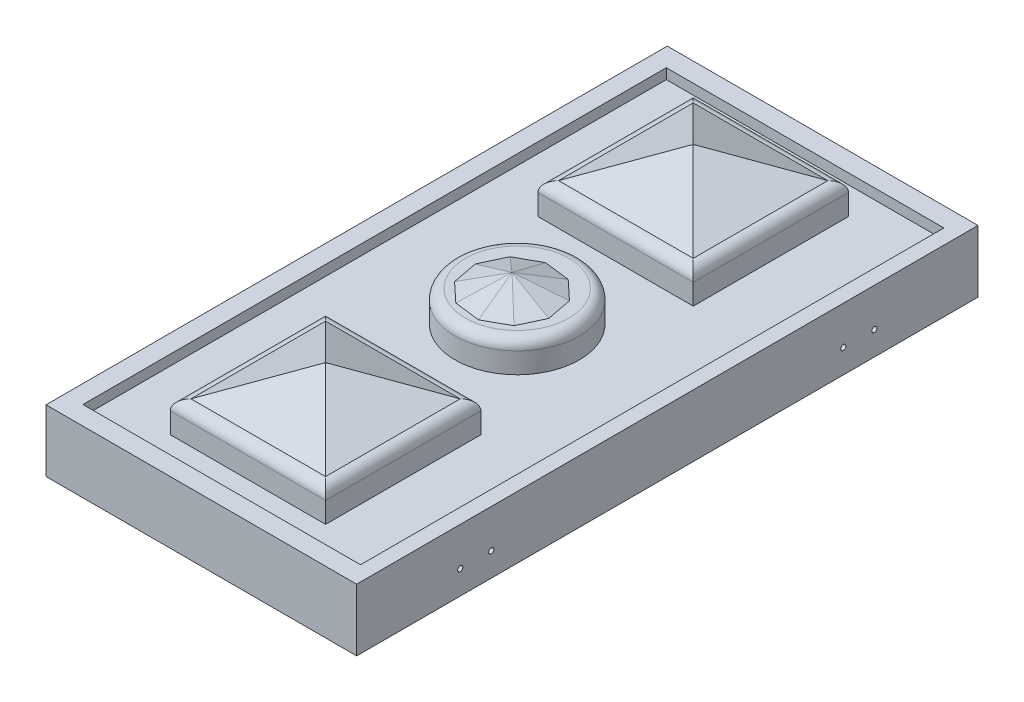
SolidWorks part; units mm, degrees
ref_plane "Front Plane" through (0, 0, 0) normal (0, 0, 1) x (1, 0, 0)
ref_plane "Top Plane" through (0, 0, 0) normal (0, 1, 0) x (1, 0, 0)
ref_plane "Right Plane" through (0, 0, 0) normal (1, 0, 0) x (0, 0, -1)
sketch "Sketch1" plane through (0, 0, 0) normal (0, 1, 0) x (1, 0, 0)
  line L1 (-150, -300) -> (150, -300)
  line L2 (-150, -300) -> (-150, 300)
  line L3 (-150, 300) -> (150, 300)
  line L4 (150, -300) -> (150, 300)
  line L5 (-150, -300) -> (150, 300) construction
  line L6 (-150, 300) -> (150, -300) construction
  point P0 (0, 0)
  dimension "D1" = 300
  dimension "D2" = 600
extrude "Boss-Extrude1" add sketch "Sketch1" along normal blind 50
sketch "Sketch2" plane through (150, 0, 0) normal (1, 0, 0) x (0, 0, -1)
  line L1 (-300, 50) -> (300, 50) construction
  circle A4 centre (-200, 22.9311) radius 2.5
  circle A5 centre (-170, 22.9311) radius 2.5
  circle A6 centre (170, 22.9311) radius 2.5
  circle A7 centre (200, 22.9311) radius 2.5
  dimension "D1" = 30
  dimension "D2" = 30
  dimension "D3" = 340
  dimension "D4" = 100
  dimension "D5" = 5
  dimension "D6" = 27.0689
extrude "Cut-Extrude1" cut sketch "Sketch2" against normal blind 50
sketch "Sketch3" plane through (0, 50, 0) normal (0, 1, 0) x (1, 0, 0)
  line L0 (150, 300) -> (-150, 300) construction
  line L1 (-80, 255) -> (70, 255)
  line L2 (-80, 255) -> (-80, 105)
  line L3 (-80, 105) -> (70, 105)
  line L4 (70, 255) -> (70, 105)
  line L5 (-75, -105) -> (75, -105)
  line L6 (-75, -105) -> (-75, -255)
  line L7 (-75, -255) -> (75, -255)
  line L8 (75, -105) -> (75, -255)
  line L9 (-150, -300) -> (150, -300) construction
  line L10 (150, -300) -> (150, 300) construction
  circle A0 centre (0, 5) radius 60
  dimension "D3" = 120
  dimension "D11" = 150
  dimension "D1" = 150
  dimension "D2" = 150
  dimension "D4" = 150
  dimension "D5" = 150
  dimension "D6" = 45
  dimension "D7" = 100
  dimension "D8" = 45
  dimension "D9" = 75
  dimension "D10" = 80
extrude "Boss-Extrude3" add sketch "Sketch3" along normal blind 30
fillet "Fillet1" radius 10 9 edges at (0, 80, 105) (75, 80, 180) (0, 80, 255) (-75, 80, 180) (0, 80, 55) (-5, 80, -255) (70, 80, -180) (-5, 80, -105) (-80, 80, -180)
sketch "Sketch4" plane through (0, 80, 0) normal (0, 1, 0) x (1, 0, 0)
  line L4 (60, 115) -> (60, 245)
  line L5 (60, 245) -> (-70, 245)
  line L6 (-70, 245) -> (-70, 115)
  line L7 (-70, 115) -> (60, 115)
  line L8 (60, 115) -> (60, 245)
  line L9 (60, 245) -> (-70, 245)
  line L10 (-70, 245) -> (-70, 115)
  line L11 (-70, 115) -> (60, 115)
  dimension "D1" = 0
extrude "Boss-Extrude4" add sketch "Sketch4" along normal blind 30 draft 65
sketch "Sketch5" plane through (0, 80, 0) normal (0, 1, 0) x (1, 0, 0)
  line L4 (65, -245) -> (65, -115)
  line L5 (65, -115) -> (-65, -115)
  line L6 (-65, -115) -> (-65, -245)
  line L7 (-65, -245) -> (65, -245)
  line L8 (65, -245) -> (65, -115)
  line L9 (65, -115) -> (-65, -115)
  line L10 (-65, -115) -> (-65, -245)
  line L11 (-65, -245) -> (65, -245)
  dimension "D1" = 0
extrude "Boss-Extrude5" add sketch "Sketch5" along normal blind 30 draft 65
sketch "Sketch6" plane through (0, 80, 0) normal (0, 1, 0) x (1, 0, 0)
  line L1 (29.8292, -27.8667) -> (40.512, -5.0115)
  line L2 (40.512, -5.0115) -> (35.7206, 19.7579)
  line L3 (35.7206, 19.7579) -> (17.2851, 36.9805)
  line L4 (17.2851, 36.9805) -> (-7.7527, 40.0778)
  line L5 (-7.7527, 40.0778) -> (-29.8292, 27.8667)
  line L6 (-29.8292, 27.8667) -> (-40.512, 5.0115)
  line L7 (-40.512, 5.0115) -> (-35.7206, -19.7579)
  line L8 (-35.7206, -19.7579) -> (-17.2851, -36.9805)
  line L9 (-17.2851, -36.9805) -> (7.7527, -40.0778)
  line L10 (7.7527, -40.0778) -> (29.8292, -27.8667)
  circle A0 centre (0, 0) radius 38.8229 construction
extrude "Boss-Extrude6" add sketch "Sketch6" along normal blind 30 draft 68
sketch "Sketch7" plane through (0, 50, 0) normal (0, 1, 0) x (1, 0, 0)
  line L0 (-150, -300) -> (150, -300) construction
  line L1 (-150, 300) -> (-132.409, 300)
  line L2 (-150, 300) -> (-150, -300)
  line L3 (-150, -300) -> (-132.409, -300)
  line L4 (-132.409, 281.4313) -> (-132.409, -281.901)
  line L6 (-132.409, -281.901) -> (135.6281, -281.901)
  line L8 (-132.409, -300) -> (150, -300)
  line L9 (150, -281.901) -> (150, -300)
  line L11 (135.6281, -281.901) -> (135.6281, 281.4313)
  line L12 (135.6281, 300) -> (150, 300)
  line L13 (150, -281.901) -> (150, 300)
  line L14 (-132.409, 281.4313) -> (135.6281, 281.4313)
  line L16 (-132.409, 300) -> (135.6281, 300)
extrude "Boss-Extrude7" add sketch "Sketch7" along normal blind 10
